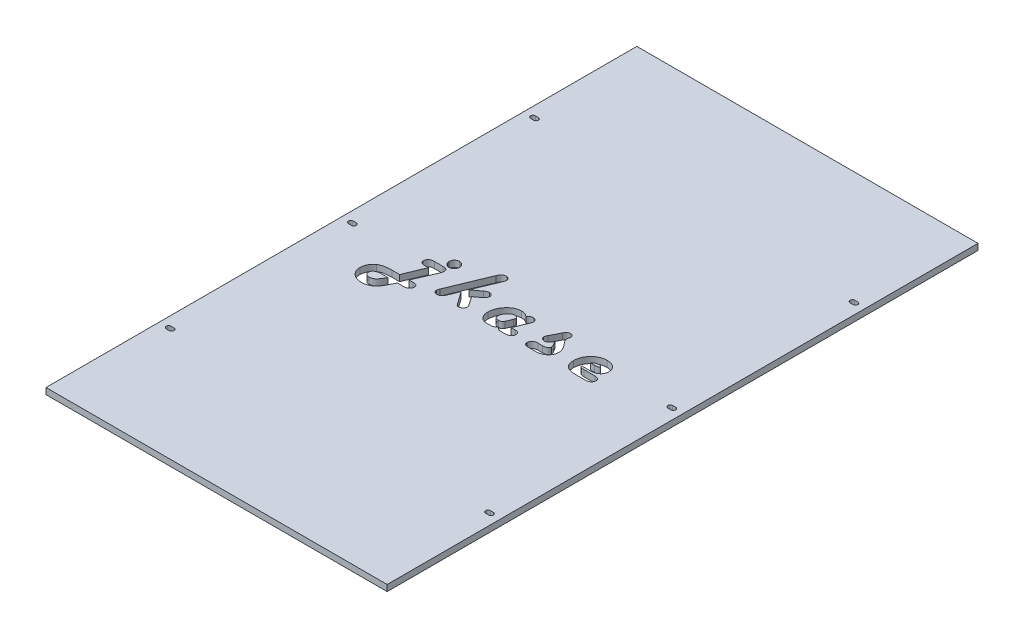
SolidWorks part; units mm, degrees
ref_plane "前基準面" through (0, 0, 0) normal (0, 0, 1) x (1, 0, 0)
ref_plane "上基準面" through (0, 0, 0) normal (0, 1, 0) x (1, 0, 0)
ref_plane "右基準面" through (0, 0, 0) normal (1, 0, 0) x (0, 0, -1)
sketch "草圖1" plane through (0, 0, 0) normal (0, 1, 0) x (1, 0, 0)
  line L0 (0, 0) -> (326.8973, 0) construction
  line L1 (0, 0) -> (0, 183.7767) construction
  line L3 (-113.7553, 194.0216) -> (106.2447, 194.0216)
  line L4 (-113.7553, 194.0216) -> (-113.7553, -186.9784)
  line L5 (-113.7553, -186.9784) -> (106.2447, -186.9784)
  line L6 (106.2447, 194.0216) -> (106.2447, -186.9784)
  dimension "D1" = 381
  dimension "D2" = 220
extrude "填料-伸長1" add sketch "草圖1" against normal blind 4
sketch "草圖2" plane through (0, 0, 0) normal (0, 1, 0) x (1, 0, 0)
  line L0 (-113.7553, 194.0216) -> (-113.7553, -186.9784) construction
  line L1 (-113.7553, -186.9784) -> (106.2447, -186.9784) construction
  line L2 (-106.7553, -113.9784) -> (99.2447, -113.9784) construction
  line L3 (-106.7553, -113.9784) -> (-106.7553, 3.5216) construction
  point P0 (-106.7553, -113.9784)
  point P6 (99.2447, -113.9784)
  point P8 (99.2447, 3.5216)
  point P9 (99.2447, 121.0216)
  point P10 (-106.7553, 3.5216)
  point P11 (-106.7553, 121.0216)
  dimension "D1" = 7
  dimension "D2" = 73
  dimension "D5" = 206
  dimension "D6" = 117.5
  dimension "D3" = 2
  dimension "D4" = 3
hole_wizard "Ø2.9 (2.9) 直徑孔1" positions "3D草圖4" profile "草圖5" hole size "Ø2.9" standard "GB" end condition through all
sketch3d "3D草圖4"
  point P0 (-106.7553, 0, -121.0216)
  point P3 (-106.7553, 0, -3.5216)
  point P6 (-106.7553, 0, 113.9784)
  point P9 (99.2447, 0, 113.9784)
  point P12 (99.2447, 0, -3.5216)
  point P15 (99.2447, 0, -121.0216)
sketch "草圖5" plane through (-106.7553, 0, -121.0216) normal (1, 0, 0) x (0, 0, 1)
  line L0 (0, 0) -> (0, 4)
  line L1 (0, 4) -> (1.45, 4)
  line L2 (1.45, 4) -> (1.45, 0)
  line L5 (1.45, 0) -> (0, 0)
  line L11 (0, -6.35) -> (0, 107.95) construction
  dimension "貫穿孔直徑" = 2.9
  dimension "貫穿孔深度" = 4
sketch "草圖7" plane through (0, 0, 0) normal (0, 1, 0) x (1, 0, 0)
  line L0 (-98.7553, -8.9784) -> (91.2447, -8.9784)
  line L1 (-113.7553, -186.9784) -> (106.2447, -186.9784) construction
  dimension "D1" = 178
sketch "草圖6" plane through (0, 0, 0) normal (0, 1, 0) x (1, 0, 0)
  text T0 "jkase" font "Harlow Solid Italic" height 33
extrude "除料-伸長3" cut sketch "草圖6" against normal through all
sketch "草圖8" plane through (0, 0, 0) normal (0, 1, 0) x (1, 0, 0)
  line L0 (-107.7553, 121.0216) -> (-105.7553, 121.0216) construction
  line L1 (-107.7553, 122.5216) -> (-105.7553, 122.5216)
  line L2 (-107.7553, 119.5216) -> (-105.7553, 119.5216)
  line L3 (98.2447, 121.0216) -> (100.2447, 121.0216) construction
  line L4 (98.2447, 122.5216) -> (100.2447, 122.5216)
  line L5 (98.2447, 119.5216) -> (100.2447, 119.5216)
  line L6 (98.2447, 3.5216) -> (100.2447, 3.5216) construction
  line L7 (98.2447, 5.0216) -> (100.2447, 5.0216)
  line L8 (98.2447, 2.0216) -> (100.2447, 2.0216)
  line L9 (98.2447, -113.9784) -> (100.2447, -113.9784) construction
  line L10 (98.2447, -112.4784) -> (100.2447, -112.4784)
  line L11 (98.2447, -115.4784) -> (100.2447, -115.4784)
  line L12 (-107.7553, 3.5216) -> (-105.7553, 3.5216) construction
  line L13 (-107.7553, 5.0216) -> (-105.7553, 5.0216)
  line L14 (-107.7553, 2.0216) -> (-105.7553, 2.0216)
  line L15 (-107.7553, -113.9784) -> (-105.7553, -113.9784) construction
  line L16 (-107.7553, -112.4784) -> (-105.7553, -112.4784)
  line L17 (-107.7553, -115.4784) -> (-105.7553, -115.4784)
  line L18 (-107.7553, 121.0216) -> (98.2447, 121.0216) construction
  line L19 (-107.7553, 121.0216) -> (-107.7553, 3.5216) construction
  arc A0 (-107.7553, 122.5216) -> (-107.7553, 119.5216) centre (-107.7553, 121.0216) ccw
  arc A1 (-105.7553, 119.5216) -> (-105.7553, 122.5216) centre (-105.7553, 121.0216) ccw
  arc A2 (98.2447, 122.5216) -> (98.2447, 119.5216) centre (98.2447, 121.0216) ccw
  arc A3 (100.2447, 119.5216) -> (100.2447, 122.5216) centre (100.2447, 121.0216) ccw
  arc A4 (98.2447, 5.0216) -> (98.2447, 2.0216) centre (98.2447, 3.5216) ccw
  arc A5 (100.2447, 2.0216) -> (100.2447, 5.0216) centre (100.2447, 3.5216) ccw
  arc A6 (98.2447, -112.4784) -> (98.2447, -115.4784) centre (98.2447, -113.9784) ccw
  arc A7 (100.2447, -115.4784) -> (100.2447, -112.4784) centre (100.2447, -113.9784) ccw
  arc A8 (-107.7553, 5.0216) -> (-107.7553, 2.0216) centre (-107.7553, 3.5216) ccw
  arc A9 (-105.7553, 2.0216) -> (-105.7553, 5.0216) centre (-105.7553, 3.5216) ccw
  arc A10 (-107.7553, -112.4784) -> (-107.7553, -115.4784) centre (-107.7553, -113.9784) ccw
  arc A11 (-105.7553, -115.4784) -> (-105.7553, -112.4784) centre (-105.7553, -113.9784) ccw
  point P2 (-106.7553, 121.0216)
  point P13 (99.2447, 121.0216)
  point P20 (99.2447, 3.5216)
  point P27 (99.2447, -113.9784)
  point P34 (-106.7553, 3.5216)
  point P41 (-106.7553, -113.9784)
  dimension "D2" = 1.5
  dimension "D1" = 2
  dimension "D5" = 206
  dimension "D6" = 117.5
  dimension "D3" = 2
  dimension "D4" = 3
extrude "除料-伸長4" cut sketch "草圖8" against normal through all
